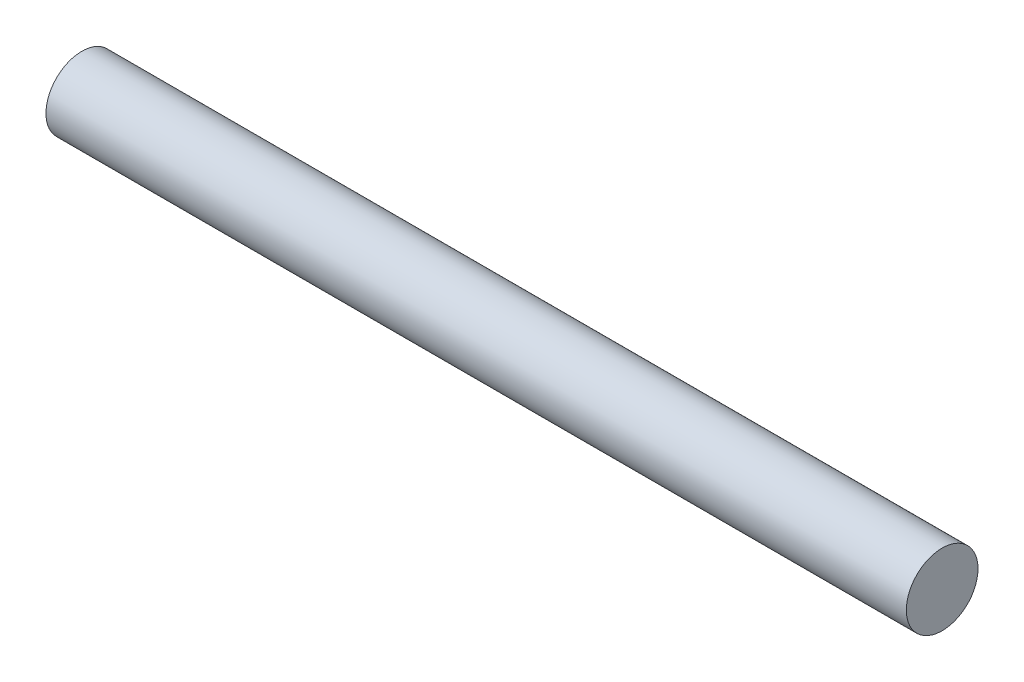
SolidWorks part; units mm, degrees
ref_plane "Front Plane" through (0, 0, 0) normal (0, 0, 1) x (1, 0, 0)
ref_plane "Top Plane" through (0, 0, 0) normal (0, 1, 0) x (1, 0, 0)
ref_plane "Right Plane" through (0, 0, 0) normal (1, 0, 0) x (0, 0, -1)
sketch "Sketch1" plane through (0, 0, 0) normal (1, 0, 0) x (0, 0, -1)
  circle A0 centre (0, 0) radius 2.3813
  dimension "D1" = 4.7625
extrude "Boss-Extrude1" add sketch "Sketch1" along normal mid plane 57.15
